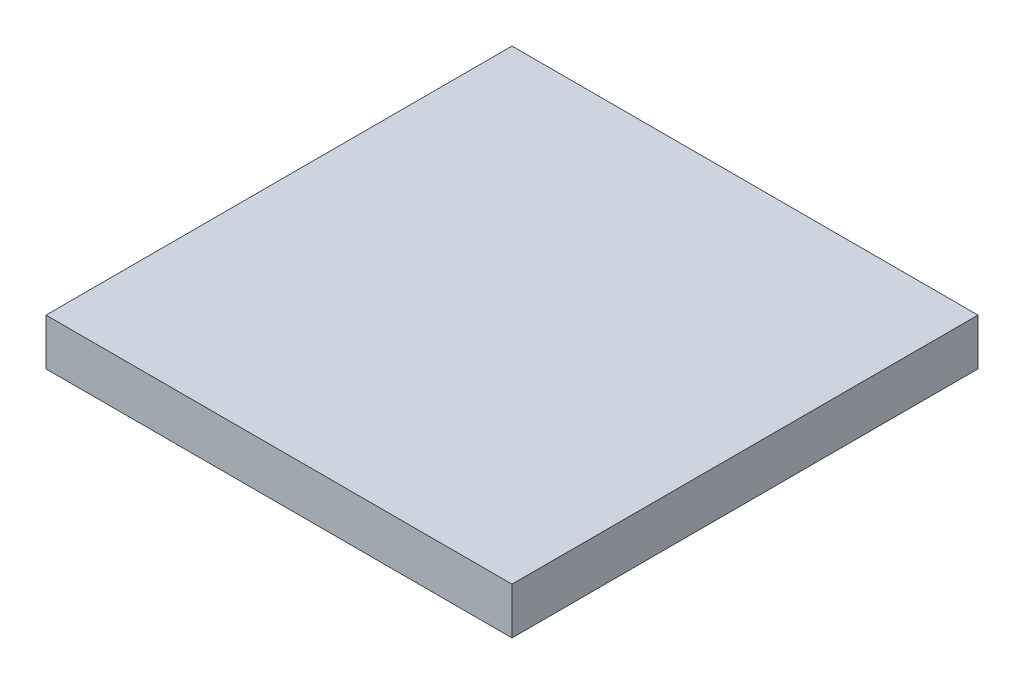
SolidWorks part; units mm, degrees
material "6061 Alloy"
ref_plane "Front Plane" through (0, 0, 0) normal (0, 0, 1) x (1, 0, 0)
ref_plane "Top Plane" through (0, 0, 0) normal (0, 1, 0) x (1, 0, 0)
ref_plane "Right Plane" through (0, 0, 0) normal (1, 0, 0) x (0, 0, -1)
sketch "Sketch1" plane through (0, 0, 0) normal (0, 1, 0) x (1, 0, 0)
  line L0 (0, 0) -> (0, 10)
  line L1 (0, 10) -> (10, 10)
  line L2 (0, 0) -> (10, 0)
  line L3 (10, 0) -> (10, 10)
  dimension "D1" = 10
  dimension "D2" = 10
extrude "Boss-Extrude1" add sketch "Sketch1" along normal blind 1
